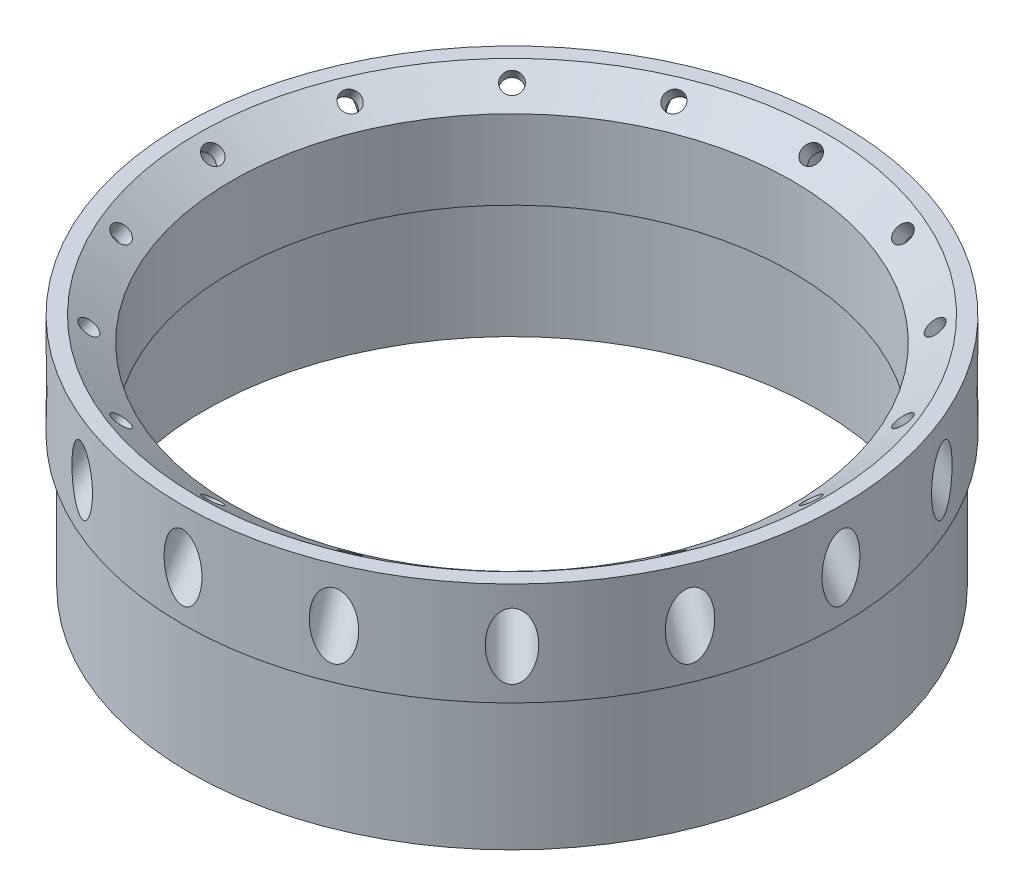
SolidWorks part; units mm, degrees
material "6061 Alloy"
ref_plane "Front Plane" through (0, 0, 0) normal (0, 0, 1) x (1, 0, 0)
ref_plane "Top Plane" through (0, 0, 0) normal (0, 1, 0) x (1, 0, 0)
ref_plane "Right Plane" through (0, 0, 0) normal (1, 0, 0) x (0, 0, -1)
sketch "Main sketch" plane through (0, 0, 0) normal (0, 0, 1) x (1, 0, 0)
  line L0 (0, 0) -> (-87, 0) construction
  line L8 (-85, -35) -> (-81, -35)
  line L23 (-87, 0) -> (-87, 27.1992)
  line L24 (-83, 27.1992) -> (-74, 20.8973)
  line L25 (-74, 20.8973) -> (-74, 0)
  line L26 (-74, 0) -> (-81, 0)
  line L27 (-81, 0) -> (-81, -35)
  line L28 (-87, 0) -> (-85, 0)
  line L29 (-85, 0) -> (-85, -35)
  line L30 (0, 0) -> (0, -35.5238) construction
  line L31 (-87, 27.1992) -> (-83, 27.1992)
  line L32 (-74, 20.8973) -> (-87, 20.8973) construction
  point P4 (-87, 30)
  dimension "D1" = 87
  dimension "D2" = 2
  dimension "D3" = 4
  dimension "D4" = 55
  dimension "D5" = 30
  dimension "D6" = 13
  dimension "D7" = 35
  dimension "D8" = 4
  dimension "D9" = 90
revolve "Main revolve" add sketch "Main sketch" angle 360 about L30
sketch "Hole position" plane through (0, 0, 0) normal (0, 0, 1) x (1, 0, 0)
  line L0 (-79, 24.3983) -> (-83, 18.6857) construction
  line L1 (-83, 27.1992) -> (-74, 20.8973) construction
  line L2 (0, 30) -> (0, -2.3509) construction
  line L4 (-83, 27.1992) -> (-83, -10.9444) construction
  line L6 (87, 30) -> (-87, 30) construction
  line L7 (-83, 18.6857) -> (-67.2656, 7.6684) construction
  point P7 (-79, 24.3983)
  dimension "D1" = 4
ref_plane "Hole plane" through (-18.5267, -26.4589, 0) normal (-0.5736, -0.8192, 0) x (0.8192, -0.5736, 0)
sketch "Sketch14" plane through (-18.5267, -26.4589, 0) normal (-0.5736, -0.8192, 0) x (0.8192, -0.5736, 0)
  circle A1 centre (-78.7073, 0) radius 5
  dimension "D1" = 5
extrude "Hole extrude 1" cut sketch "Sketch14" against normal blind 3 and the other way through all
hole_wizard "screw extrude" positions "3DSketch13" profile "Sketch15" hole size "Ø5.0" standard "DIN" end condition up to next
sketch3d "3DSketch13"
  line L0 (-79, 24.3983, 0) -> (-83, 18.6857, 0) construction
  point P0 (-81.2793, 21.1432, 0)
sketch "Sketch15" plane through (-81.2793, 21.1432, 0) normal (0, 0, 1) x (0.8192, -0.5736, 0)
  line L0 (0, 0) -> (0, 3.9738)
  line L1 (0, 3.9738) -> (2.5, 3.9738)
  line L2 (2.5, 3.9738) -> (2.5, 0)
  line L5 (2.5, 0) -> (0, 0)
  line L11 (0, -6.35) -> (0, 107.95) construction
  dimension "Thru Hole Dia." = 5
  dimension "Thru Hole Depth" = 3.9738
pattern_circular "Screw holes pattern" count 16 over 360 about axis through (0, 0, 0) along (0, 1, 0) of "Hole extrude 1", "screw extrude"
